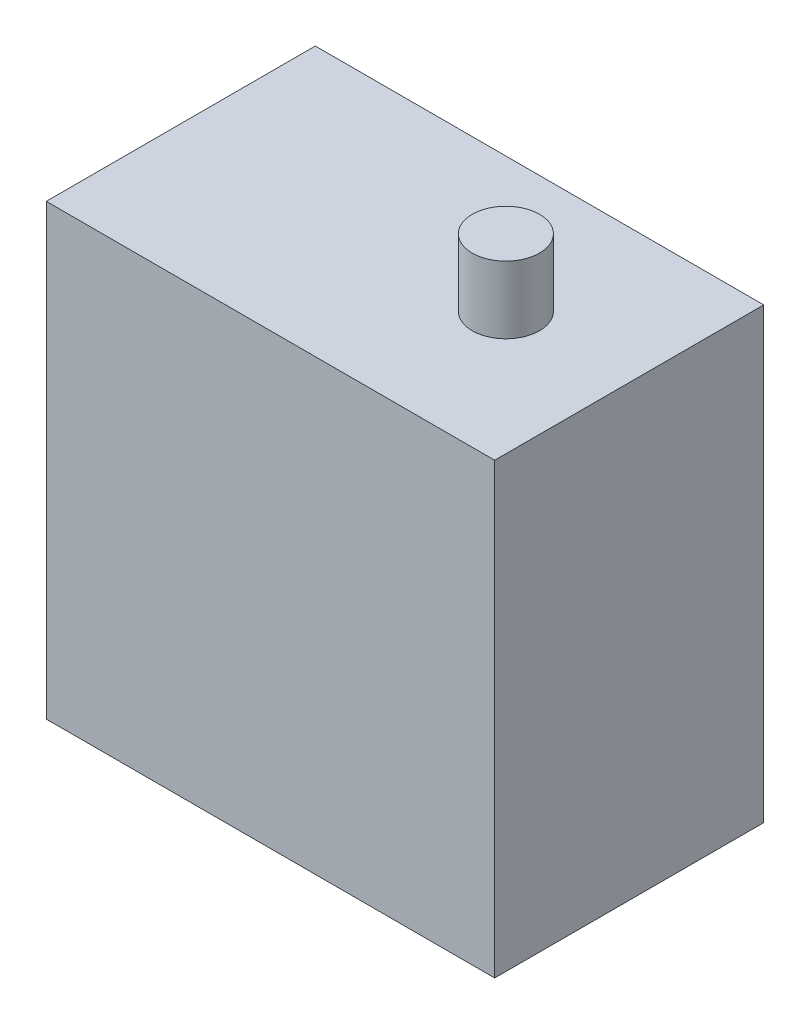
SolidWorks part; units mm, degrees
ref_plane "Front Plane" through (0, 0, 0) normal (0, 0, 1) x (1, 0, 0)
ref_plane "Top Plane" through (0, 0, 0) normal (0, 1, 0) x (1, 0, 0)
ref_plane "Right Plane" through (0, 0, 0) normal (1, 0, 0) x (0, 0, -1)
sketch "Sketch1" plane through (0, 0, 0) normal (0, 1, 0) x (1, 0, 0)
  line L1 (-10, 6) -> (10, 6)
  line L2 (-10, 6) -> (-10, -6)
  line L3 (-10, -6) -> (10, -6)
  line L4 (10, 6) -> (10, -6)
  line L5 (-10, 6) -> (10, -6) construction
  line L6 (-10, -6) -> (10, 6) construction
  point P0 (0, 0)
  dimension "D1" = 12
  dimension "D2" = 20
extrude "Boss-Extrude1" add sketch "Sketch1" along normal blind 20
sketch "Sketch2" plane through (0, 20, 0) normal (0, 1, 0) x (1, 0, 0)
  line L0 (10, -6) -> (10, 6) construction
  circle A0 centre (4.5, 0) radius 1.5
  dimension "D1" = 3
  dimension "D2" = 5.5
extrude "Boss-Extrude2" add sketch "Sketch2" along normal blind 3
